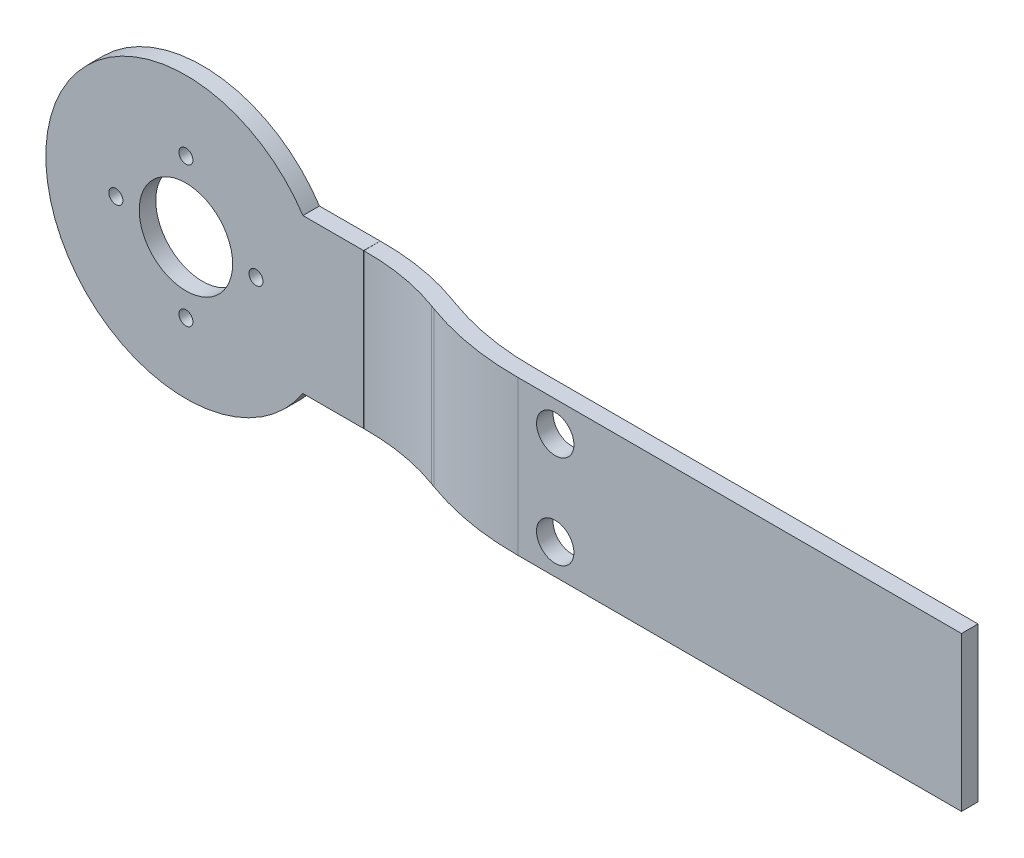
SolidWorks part; units mm, degrees
ref_plane "前视基准面" through (0, 0, 0) normal (0, 0, 1) x (1, 0, 0)
ref_plane "上视基准面" through (0, 0, 0) normal (0, 1, 0) x (1, 0, 0)
ref_plane "右视基准面" through (0, 0, 0) normal (1, 0, 0) x (0, 0, -1)
sketch "Sketch1" plane through (0, 0, 0) normal (0, 0, 1) x (1, 0, 0)
  circle A0 centre (0, 0) radius 30
extrude "Boss-Extrude1" add sketch "Sketch1" along normal blind 3.54
sketch "Sketch3" plane through (0, 0, 3.54) normal (0, 0, 1) x (1, 0, 0)
  circle A1 centre (12, 5) radius 4
  dimension "D1" = 5
  dimension "D2" = 12
sketch "Sketch4" plane through (0, 0, 3.54) normal (0, 0, 1) x (1, 0, 0)
  line L0 (25.7688, 0) -> (75.3766, 0) construction
  line L1 (25.0549, 16.5) -> (38.0549, 16.5)
  line L2 (25.0549, -16.5) -> (38.0549, -16.5)
  line L3 (30, 0) -> (30, 16.5) construction
  line L4 (38.0549, 16.5) -> (38.0549, -16.5)
  circle A0 centre (0, 0) radius 30 construction
  arc A1 (25.0549, 16.5) -> (25.0549, -16.5) centre (0, 0) cw
  dimension "D1" = 16.5
  dimension "D2" = 13
extrude "Boss-Extrude4" add sketch "Sketch4" against normal blind 3.54
sketch "Sketch5" plane through (0, 0, 3.54) normal (0, 0, 1) x (1, 0, 0)
  circle A0 centre (0, 0) radius 10
  dimension "D1" = 20
extrude "Cut-Extrude1" cut sketch "Sketch5" against normal up to next
sketch "Sketch6" plane through (0, 0, 3.54) normal (0, 0, 1) x (1, 0, 0)
  circle A8 centre (0, 15) radius 1.5
  circle A9 centre (15, 0) radius 1.5
  circle A10 centre (0, 0) radius 15 construction
  circle A11 centre (0, -15) radius 1.5
  circle A12 centre (-15, 0) radius 1.5
  dimension "D1" = 4
extrude "Cut-Extrude2" cut sketch "Sketch6" against normal up to next
sketch "Sketch7" plane through (0, 16.5, 0) normal (0, 1, 0) x (1, 0, 0)
  line L0 (78.0549, -7) -> (173.0549, -7)
  line L1 (38.0549, 0) -> (25.0549, 0) construction
  line L2 (38.0549, 0) -> (38.0549, -3.54) construction
  line L3 (55.497, -6.4884) -> (56.408, -6.82)
  line L4 (56.7077, -3.1619) -> (57.6187, -3.4934)
  line L5 (78.071, -10.54) -> (173.0549, -10.54)
  line L6 (38.0549, 0) -> (38.1018, -3.5397)
  line L7 (173.0549, -7) -> (173.0549, -10.54)
  arc A0 (38.0549, 0) -> (56.7077, -3.1619) centre (38.7498, -52.5007) cw
  arc A1 (78.0549, -7) -> (57.6187, -3.4934) centre (77.5194, 51.1832) cw
  arc A2 (38.1018, -3.5397) -> (55.497, -6.4884) centre (38.7498, -52.5007) cw
  arc A3 (78.071, -10.54) -> (56.408, -6.82) centre (77.5194, 51.1832) cw
  dimension "D1" = 7
  dimension "D2" = 40
  dimension "D3" = 3.54
  dimension "D4" = 95
extrude "Boss-Extrude5" add sketch "Sketch7" against normal up to surface (33 mm away) separate body up to face at (31.5549, -16.5, 1.77)
sketch "Sketch8" plane through (0, 0, 10.54) normal (0, 0, 1) x (1, 0, 0)
  line L0 (86.071, 15.4413) -> (86.071, -8.4863) construction
  line L1 (93.673, 0) -> (79.5285, 0) construction
  line L2 (78.071, -16.5) -> (78.071, 16.5) construction
  circle A0 centre (86.071, 10) radius 4
  circle A1 centre (86.071, -10) radius 4
  dimension "D1" = 10
  dimension "D2" = 8
extrude "Cut-Extrude3" cut sketch "Sketch8" against normal blind 10
